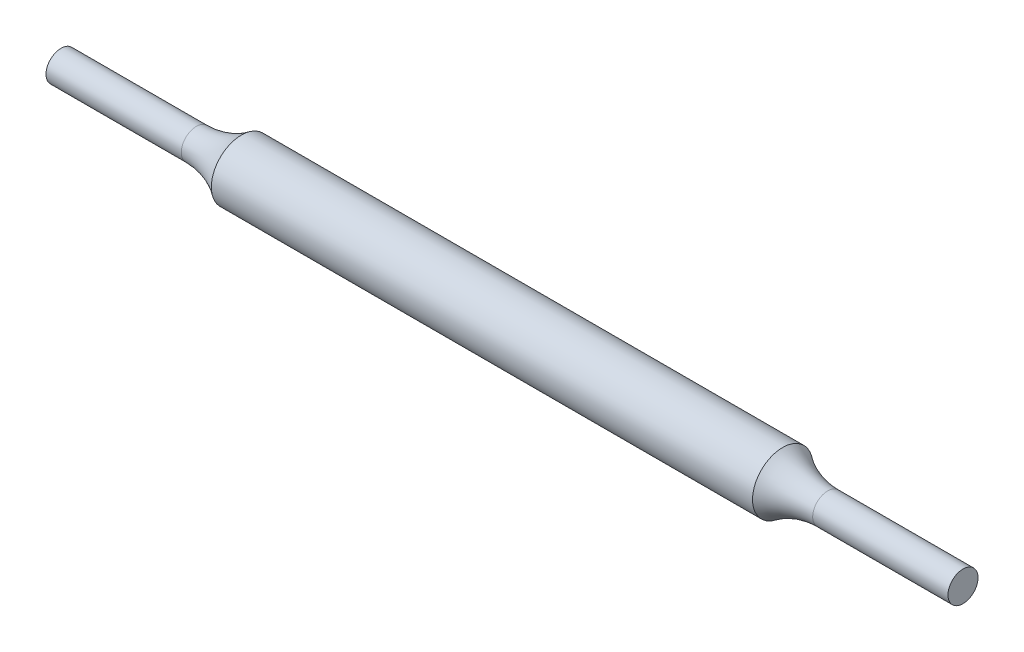
SolidWorks part; units mm, degrees
ref_plane "Front Plane" through (0, 0, 0) normal (0, 0, 1) x (1, 0, 0)
ref_plane "Top Plane" through (0, 0, 0) normal (0, 1, 0) x (1, 0, 0)
ref_plane "Right Plane" through (0, 0, 0) normal (1, 0, 0) x (0, 0, -1)
sketch "Sketch1" plane through (0, 0, 0) normal (0, 1, 0) x (1, 0, 0)
  line L0 (0, 0) -> (60, 0)
  line L1 (60, 0) -> (60, 1)
  line L2 (0, 0) -> (0, 1)
  line L3 (0, 1) -> (9, 1)
  line L4 (60, 1) -> (51, 1)
  line L5 (12, 2) -> (48, 2)
  arc A0 (9, 1) -> (12, 2) centre (9, 6) ccw
  arc A2 (51, 1) -> (48, 2) centre (51, 6) cw
  dimension "D1" = 60
  dimension "D2" = 1
  dimension "D3" = 1
  dimension "D4" = 9
  dimension "D5" = 9
  dimension "D6" = 3
  dimension "D7" = 3
  dimension "D8" = 2
revolve "Revolve2" add sketch "Sketch1" angle 360 about L0
